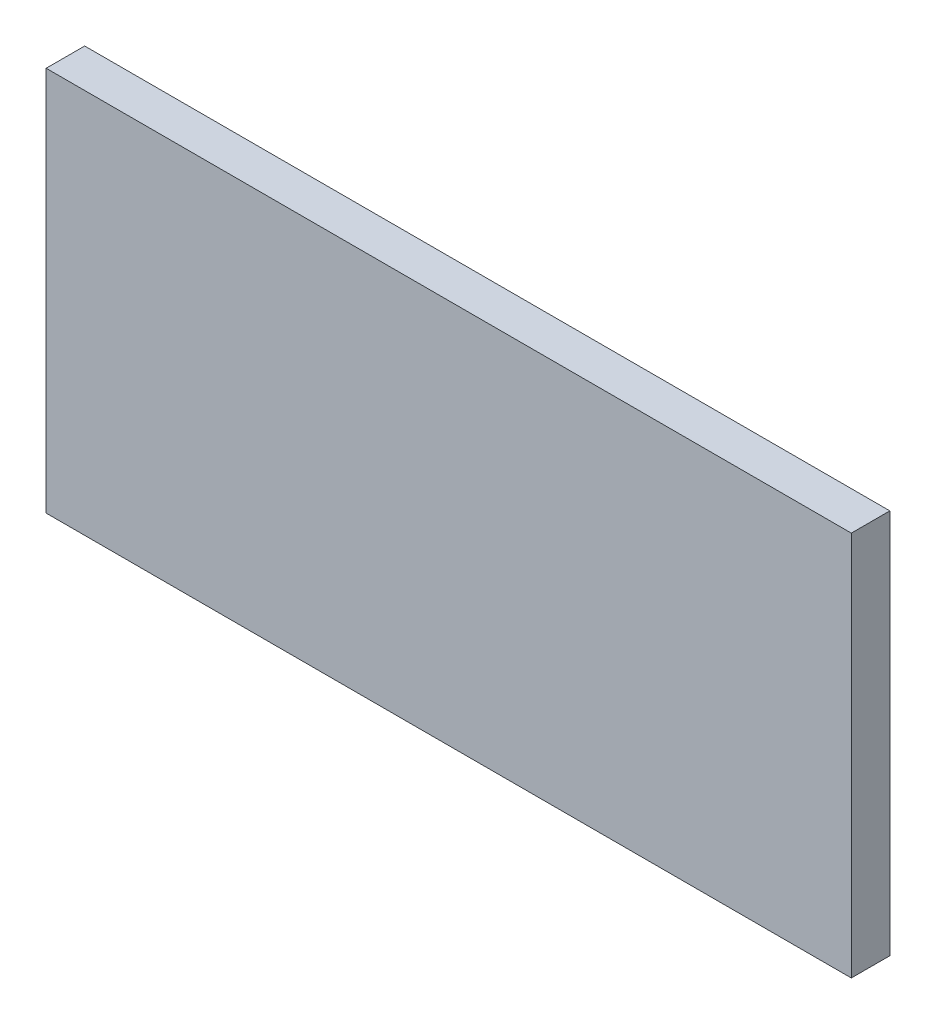
SolidWorks part; units mm, degrees
ref_plane "Front Plane" through (0, 0, 0) normal (0, 0, 1) x (1, 0, 0)
ref_plane "Top Plane" through (0, 0, 0) normal (0, 1, 0) x (1, 0, 0)
ref_plane "Right Plane" through (0, 0, 0) normal (1, 0, 0) x (0, 0, -1)
sketch "Sketch1" plane through (0, 0, 0) normal (0, 0, 1) x (1, 0, 0)
  line L1 (33.1749, -15.875) -> (-33.1749, -15.875)
  line L2 (33.1749, -15.875) -> (33.1749, 15.875)
  line L3 (33.1749, 15.875) -> (-33.1749, 15.875)
  line L4 (-33.1749, -15.875) -> (-33.1749, 15.875)
  line L5 (33.1749, -15.875) -> (-33.1749, 15.875) construction
  line L6 (33.1749, 15.875) -> (-33.1749, -15.875) construction
  point P0 (0, 0)
  dimension "D1" = 66.3499
  dimension "D2" = 31.75
extrude "Boss-Extrude1" add sketch "Sketch1" along normal blind 3.175
